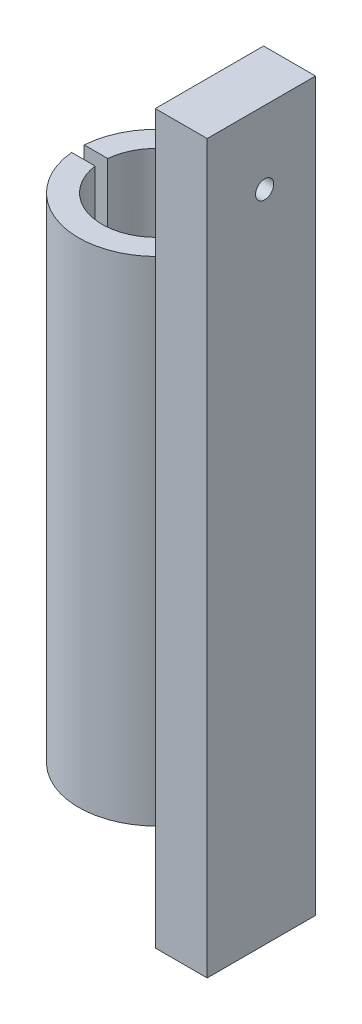
SolidWorks part; units mm, degrees
ref_plane "前视基准面" through (0, 0, 0) normal (0, 0, 1) x (1, 0, 0)
ref_plane "上视基准面" through (0, 0, 0) normal (0, 1, 0) x (1, 0, 0)
ref_plane "右视基准面" through (0, 0, 0) normal (1, 0, 0) x (0, 0, -1)
sketch "草图1" plane through (0, 0, 0) normal (0, 1, 0) x (1, 0, 0)
  circle A0 centre (0, 0) radius 15
  dimension "D1" = 30
extrude "凸台-拉伸1" add sketch "草图1" along normal blind 95 contours A0
sketch "草图2" plane through (0, 95, 0) normal (0, 1, 0) x (1, 0, 0)
  circle A0 centre (0, 0) radius 10.5
  point P3 (0, 0)
  dimension "D1" = 21
extrude "切除-拉伸1" cut sketch "草图2" against normal blind 95
sketch "草图3" plane through (0, 0, 0) normal (0, -1, 0) x (-1, 0, 0)
  line L1 (-10.8084, -11.0623) -> (-20.8084, -11.0623)
  line L2 (-10.8084, -11.0623) -> (-10.8084, 9.7991)
  line L3 (-10.8084, 9.7991) -> (-20.8084, 9.7991)
  line L4 (-20.8084, -11.0623) -> (-20.8084, 9.7991)
  point P4 (0, 0)
  dimension "D1" = 10
extrude "凸台-拉伸2" add sketch "草图3" along normal blind 20 and the other way blind 120 contours L2 L1 L4 L3
sketch "草图5" plane through (0, 0, -9.7991) normal (0, 0, -1) x (-1, 0, 0)
  line L0 (-11.3569, 95) -> (-11.3569, 75)
  line L1 (-11.3569, 95) -> (-11.3569, 0) construction
  line L2 (-11.3569, 0) -> (-11.3569, 35)
  dimension "D1" = 20
  dimension "D2" = 35
sketch "草图7" plane through (0, 0, 11.0623) normal (0, 0, 1) x (1, 0, 0)
  line L0 (-15, 95) -> (-15, 0) construction
  line L1 (-15, 35) -> (0, 35)
  line L2 (-15, 35) -> (-15, 75)
  line L3 (-15, 75) -> (0, 75)
  line L4 (0, 35) -> (0, 75)
extrude "切除-拉伸3" cut sketch "草图7" against normal through all
sketch "草图8" plane through (0, 95, 0) normal (0, 1, 0) x (1, 0, 0)
  line L1 (-17.9321, 1.0344) -> (-9.8861, 1.0344)
  line L2 (-17.9321, 1.0344) -> (-17.9321, -1.4348)
  line L3 (-17.9321, -1.4348) -> (-9.8861, -1.4348)
  line L4 (-9.8861, 1.0344) -> (-9.8861, -1.4348)
extrude "切除-拉伸4" cut sketch "草图8" against normal through all
sketch "草图9" plane through (0, 0, -9.7991) normal (0, 0, -1) x (-1, 0, 0)
  line L0 (-10.8084, 95) -> (-10.8084, 106)
  dimension "D1" = 11
sketch "草图10" plane through (10.8084, 0, 0) normal (-1, 0, 0) x (0, 0, 1)
  circle A0 centre (0, 106) radius 1.75
  dimension "D1" = 3.5
extrude "切除-拉伸5" cut sketch "草图10" against normal through all
